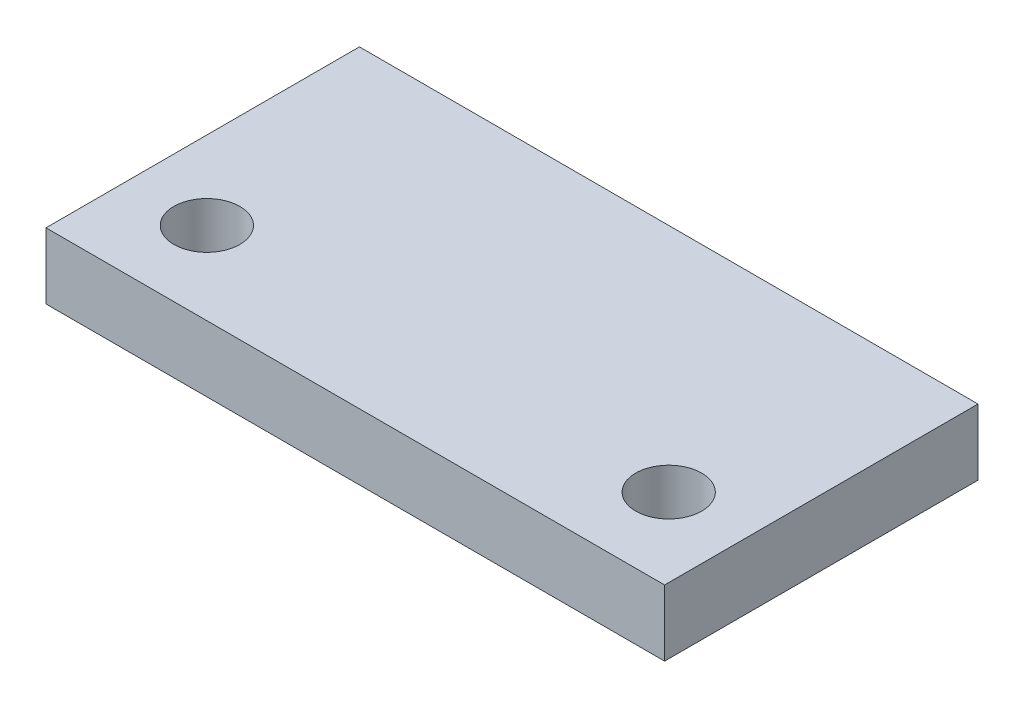
SolidWorks part; units mm, degrees
ref_plane "Front Plane" through (0, 0, 0) normal (0, 0, 1) x (1, 0, 0)
ref_plane "Top Plane" through (0, 0, 0) normal (0, 1, 0) x (1, 0, 0)
ref_plane "Right Plane" through (0, 0, 0) normal (1, 0, 0) x (0, 0, -1)
sketch "Sketch1" plane through (0, 0, 0) normal (0, 0, 1) x (1, 0, 0)
  line L0 (-37.5, 0) -> (37.5, 0)
  line L1 (-37.5, 0) -> (-37.5, -8)
  line L2 (-37.5, -8) -> (37.5, -8)
  line L3 (37.5, -8) -> (37.5, 0)
  line L4 (0, 0) -> (0, -8) construction
  dimension "D1" = 8
  dimension "D2" = 75
extrude "Boss-Extrude1" add sketch "Sketch1" along normal blind 38
sketch "Sketch2" plane through (0, 0, 0) normal (0, 1, 0) x (1, 0, 0)
  line L0 (-37.5, -28) -> (37.5, -28) construction
  line L3 (0, 0) -> (0, -38) construction
  line L4 (37.5, 0) -> (-37.5, 0) construction
  line L5 (37.5, -38) -> (-37.5, -38) construction
  line L6 (-37.5, -38) -> (-37.5, 0) construction
  line L7 (37.5, -38) -> (37.5, 0) construction
  circle A0 centre (-28, -28) radius 4
  circle A1 centre (28, -28) radius 4
  point P16 (0, 0)
  dimension "D1" = 56
  dimension "D2" = 8
  dimension "D3" = 10
extrude "Cut-Extrude1" cut sketch "Sketch2" against normal through all both and the other way through all
